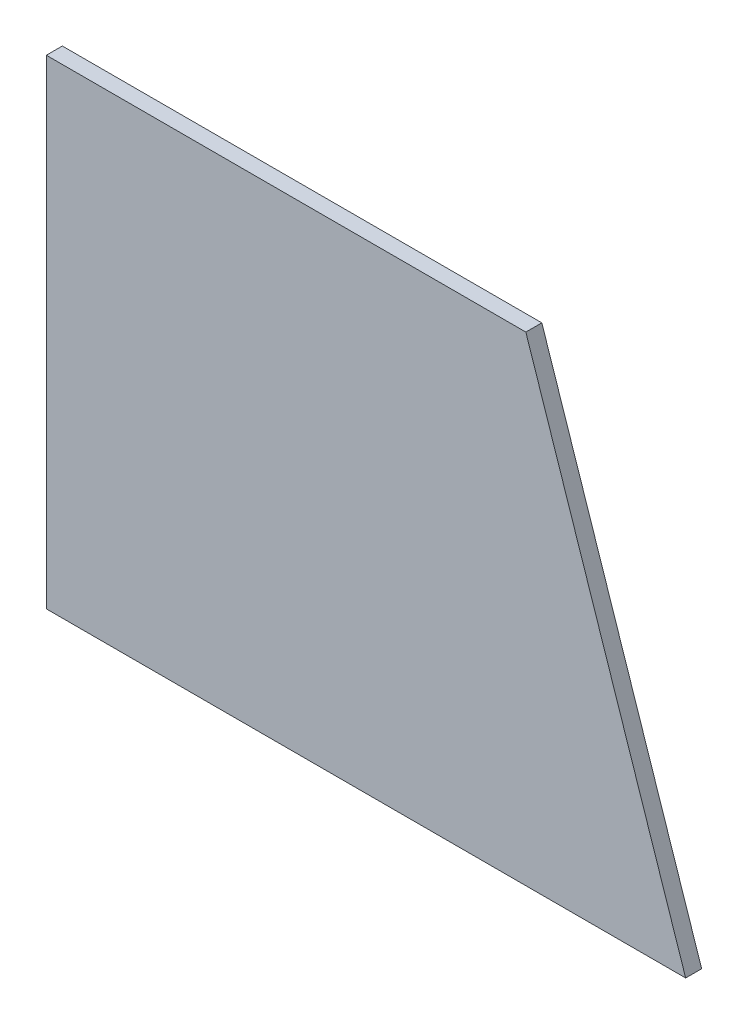
SolidWorks part; units mm, degrees
ref_plane "Front Plane" through (0, 0, 0) normal (0, 0, 1) x (1, 0, 0)
ref_plane "Top Plane" through (0, 0, 0) normal (0, 1, 0) x (1, 0, 0)
ref_plane "Right Plane" through (0, 0, 0) normal (1, 0, 0) x (0, 0, -1)
sketch "Sketch1" plane through (0, 0, 0) normal (0, 0, 1) x (1, 0, 0)
  line L0 (0, 0.6) -> (0, 0)
  line L1 (0, 0) -> (0.8, 0)
  line L2 (0.8, 0) -> (0.6, 0.6)
  line L3 (0.6, 0.6) -> (0, 0.6)
  dimension "D1" = 0.6
  dimension "D2" = 0.8
sketch "Sketch3" plane through (0, 0, 0) normal (1, 0, 0) x (0, 0, -1)
  line L0 (-0.025, 0.6) -> (0.025, 0.6)
  arc A0 (0.025, 0.6) -> (-0.025, 0.6) centre (0, 0.6) ccw
  dimension "D1" = 0.05
extrude "Boss-Extrude1" add sketch "Sketch1" along normal mid plane 0.02
